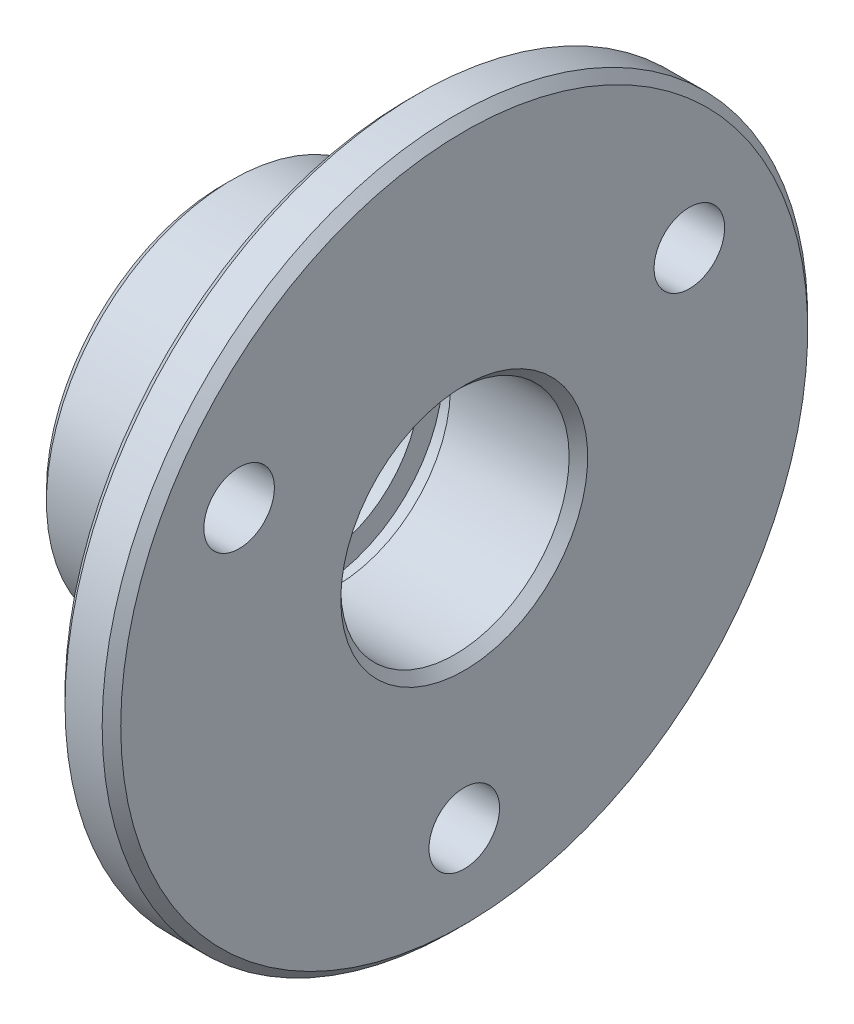
SolidWorks part; units mm, degrees
ref_plane "Front Plane" through (0, 0, 0) normal (0, 0, 1) x (1, 0, 0)
ref_plane "Top Plane" through (0, 0, 0) normal (0, 1, 0) x (1, 0, 0)
ref_plane "Right Plane" through (0, 0, 0) normal (1, 0, 0) x (0, 0, -1)
sketch "Sketch2" plane through (0, 0, 0) normal (1, 0, 0) x (0, 0, -1)
  circle A0 centre (0, 0) radius 10
  dimension "D1" = 20
extrude "Boss-Extrude1" add sketch "Sketch2" along normal offset from surface (13 mm away) 3
hole_wizard "Ø11.0 (11) M12x0.5 tapped hole" positions "3DSketch2" profile "Sketch3" hole size "Ø11.0" standard "ISO" end condition through all
sketch3d "3DSketch2"
  point P0 (0, 0, 0)
sketch "Sketch3" plane through (0, 0, 0) normal (0, 1, 0) x (0, 0, 1)
  line L0 (0, 0) -> (0, 13)
  line L1 (0, 13) -> (5.5, 13)
  line L2 (5.5, 13) -> (5.5, 0)
  line L5 (5.5, 0) -> (0, 0)
  line L11 (0, -6.35) -> (0, 107.95) construction
  dimension "Thru Hole Dia." = 11
  dimension "Thru Hole Depth" = 13
chamfer "Chamfer1" distance 0.5 angle 45 1 edges at (0, 0, 5.5)
ref_plane "Plane1" through (5.105, 0, 0) normal (-1, 0, 0) x (0, 0, 1)
sketch "Sketch4" plane through (13, 0, 0) normal (1, 0, 0) x (0, 0, -1)
  circle A0 centre (0, 0) radius 6.15
  dimension "D1" = 12.3
extrude "Cut-Extrude8" cut sketch "Sketch4" against normal up to surface (7.895 mm away)
sketch "Sketch5" plane through (5.105, 0, 0) normal (1, 0, 0) x (0, 0, -1)
  circle A0 centre (0, 0) radius 6.75
  circle A1 centre (0, 0) radius 6.15 construction
  dimension "D1" = 0.6
extrude "Cut-Extrude9" cut sketch "Sketch5" along normal blind 1
sketch "Sketch6" plane through (10, 0, 0) normal (1, 0, 0) x (0, 0, -1)
  circle A0 centre (0, 0) radius 19
  circle A1 centre (0, 0) radius 10 construction
  circle A3 centre (0, 0) radius 6.15
  circle A4 centre (0, 0) radius 6.15
  dimension "D1" = 38
  dimension "D2" = 0
extrude "Boss-Extrude2" add sketch "Sketch6" along normal blind 3
chamfer "Chamfer2" distance 0.5 angle 45 1 edges at (13, 0, -6.15)
hole_wizard "M3 Tapped Hole1" positions "3DSketch3" profile "Sketch7" tap size "M3" standard "ISO"
sketch3d "3DSketch3"
  line L0 (6.9465, 17.4809, 0) -> (6.9465, -11.0941, 0) construction
  point P0 (6.9465, 10, 0)
sketch "Sketch7" plane through (6.9465, 10, 0) normal (1, 0, 0) x (0, 0, 1)
  line L0 (0, 0) -> (0, 3.85)
  line L1 (0, 3.85) -> (1.25, 3.85)
  line L2 (1.25, 3.85) -> (1.25, 0)
  line L5 (1.25, 0) -> (0, 0)
  line L11 (0, -6.35) -> (0, 107.95) construction
  dimension "Thru Tap Drill Dia." = 2.5
  dimension "Thru Tap Drill Depth" = 3.85
cosmetic thread "Hole Thread1" parameters "D2"=3
sketch "Sketch9" plane through (13, 0, 0) normal (1, 0, 0) x (0, 0, -1)
  line L0 (0, 7.15) -> (0, -7.15) construction
  point P0 (0, -14)
  dimension "D1" = 14
hole_wizard "Ø3.8 (3.8) Diameter Hole1" positions "3DSketch4" profile "Sketch10" hole size "Ø3.8" standard "ISO" end condition through all
sketch3d "3DSketch4"
  point P0 (13, -14, 0)
sketch "Sketch10" plane through (13, -14, 0) normal (0, 1, 0) x (0, 0, -1)
  line L0 (0, 0) -> (0, 13)
  line L1 (0, 13) -> (1.9, 13)
  line L2 (1.9, 13) -> (1.9, 0)
  line L5 (1.9, 0) -> (0, 0)
  line L11 (0, -6.35) -> (0, 107.95) construction
  dimension "Thru Hole Dia." = 3.8
  dimension "Thru Hole Depth" = 13
pattern_circular "CirPattern1" count 3 over 360 about axis through (0, 0, 0) along (1, 0, 0) of "Ø3.8 (3.8) Diameter Hole1"
chamfer "Chamfer4" distance 0.5 angle 45 3 edges at (10, 0, -19) (13, 0, -19) (0, 0, -10)
